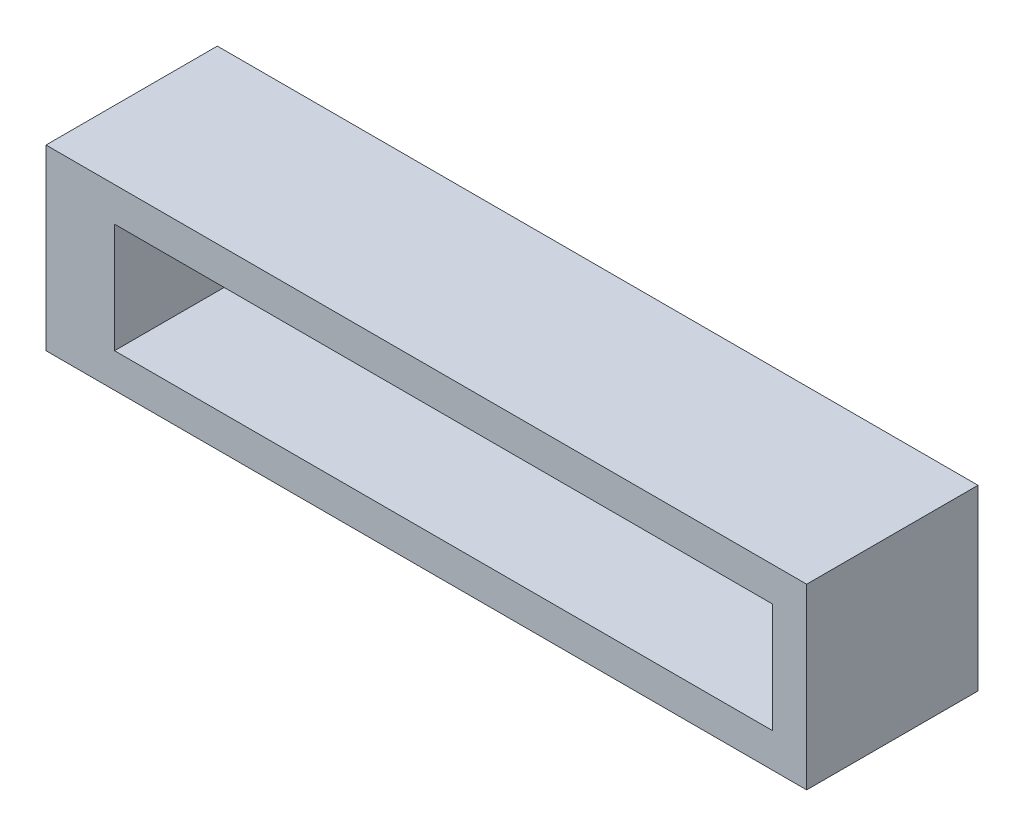
SolidWorks part; units mm, degrees
ref_plane "Přední rovina" through (0, 0, 0) normal (0, 0, 1) x (1, 0, 0)
ref_plane "Horní rovina" through (0, 0, 0) normal (0, 1, 0) x (1, 0, 0)
ref_plane "Pravá rovina" through (0, 0, 0) normal (1, 0, 0) x (0, 0, -1)
sketch "Skica1" plane through (0, 0, 0) normal (0, 0, 1) x (1, 0, 0)
  line L1 (0, 0) -> (22.2, 0)
  line L2 (0, 0) -> (0, 5.2)
  line L3 (0, 5.2) -> (22.2, 5.2)
  line L4 (22.2, 0) -> (22.2, 5.2)
  line L5 (2, 1) -> (21.2, 1)
  line L6 (2, 1) -> (2, 4.2)
  line L7 (2, 4.2) -> (21.2, 4.2)
  line L8 (21.2, 1) -> (21.2, 4.2)
  point P9 (0, 2.6)
  dimension "D1" = 2
  dimension "D2" = 1
  dimension "D3" = 1
  dimension "D4" = 1
  dimension "D5" = 22.2
  dimension "D6" = 5.2
extrude "Přidat vysunutím1" add sketch "Skica1" along normal blind 5
